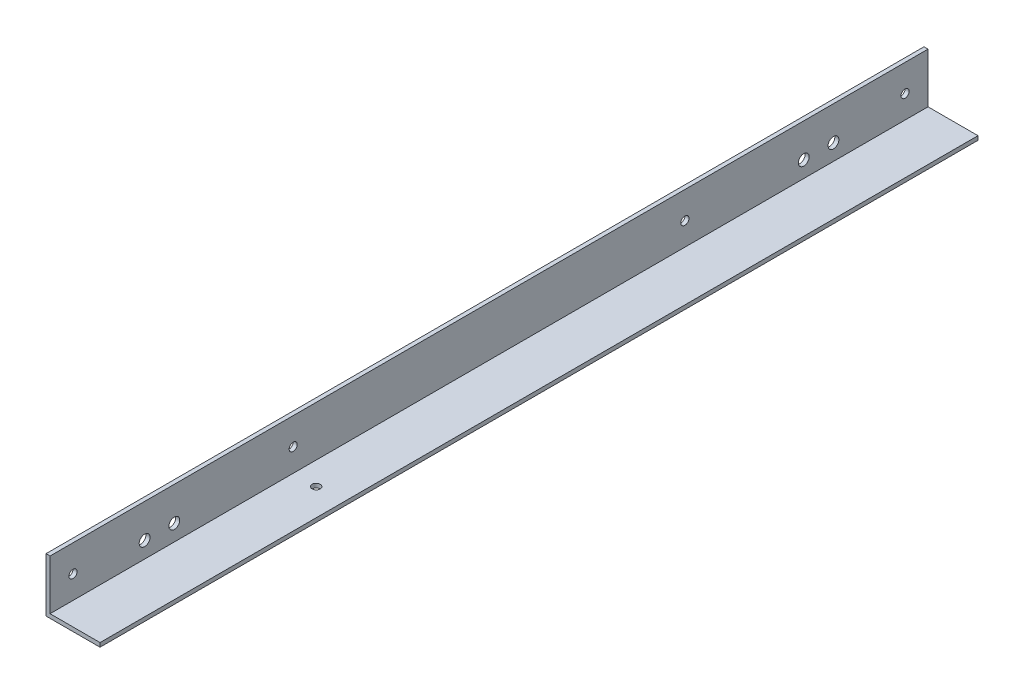
SolidWorks part; units mm, degrees
ref_plane "Plan de face" through (0, 0, 0) normal (0, 0, 1) x (1, 0, 0)
ref_plane "Plan de dessus" through (0, 0, 0) normal (0, 1, 0) x (1, 0, 0)
ref_plane "Plan de droite" through (0, 0, 0) normal (1, 0, 0) x (0, 0, -1)
sketch "Esquisse1" plane through (0, 0, 0) normal (0, 0, 1) x (1, 0, 0)
  line L0 (-17.4317, 4.7734) -> (-17.4317, -15.2266)
  line L1 (-17.4317, -15.2266) -> (2.5683, -15.2266)
  line L2 (2.5683, -15.2266) -> (2.5683, -13.7266)
  line L3 (2.5683, -13.7266) -> (-15.9317, -13.7266)
  line L4 (-15.9317, -13.7266) -> (-15.9317, 4.7734)
  line L5 (-15.9317, 4.7734) -> (-17.4317, 4.7734)
  dimension "D1" = 1.5
  dimension "D2" = 1.5
  dimension "D3" = 20
  dimension "D4" = 20
extrude "Extrusion1" add sketch "Esquisse1" along normal blind 325
sketch "Esquisse3" plane through (-15.9317, 0, 0) normal (1, 0, 0) x (0, 0, -1)
  line L0 (-316.5, -5.2266) -> (-8.5, -5.2266) construction
  line L1 (-325, -13.7266) -> (-325, 4.7734) construction
  line L2 (0, -13.7266) -> (0, 4.7734) construction
  line L3 (-325, 4.7734) -> (0, 4.7734) construction
  line L4 (-290, -7.7266) -> (-279, -7.7266) construction
  line L5 (-46, -7.7266) -> (-35, -7.7266) construction
  line L6 (0, -13.7266) -> (0, 4.7734) construction
  line L7 (-325, -13.7266) -> (0, -13.7266) construction
  circle A0 centre (-316.5, -5.2266) radius 1.5
  circle A1 centre (-8.5, -5.2266) radius 1.5
  circle A2 centre (-35, -7.7266) radius 2
  circle A3 centre (-46, -7.7266) radius 2
  circle A4 centre (-290, -7.7266) radius 2
  circle A5 centre (-279, -7.7266) radius 2
  circle A6 centre (-235, -5.2266) radius 1.5
  circle A7 centre (-90, -5.2266) radius 1.5
  dimension "D1" = 8.5
  dimension "D4" = 11
  dimension "D9" = 6
  dimension "D6" = 11
  dimension "D8" = 6
  dimension "D10" = 90
  dimension "D2" = 8.5
  dimension "D3" = 10
  dimension "D5" = 35
  dimension "D7" = 35
  dimension "D11" = 90
extrude "Extrusion3" cut sketch "Esquisse3" against normal blind 300
sketch "Esquisse4" plane through (0, -15.2266, 0) normal (0, -1, 0) x (1, 0, 0)
  line L2 (-17.4317, 325) -> (2.5683, 325) construction
  line L3 (-17.4317, 325) -> (-17.4317, 0) construction
  line L10 (-17.4317, 0) -> (2.5683, 0) construction
  circle A0 centre (-7.4317, 235) radius 1.5
  point P6 (0, 0)
  point P8 (-7.4317, 0)
  dimension "D1" = 90
  dimension "D2" = 10
extrude "Extrusion5" cut sketch "Esquisse4" against normal blind 10
